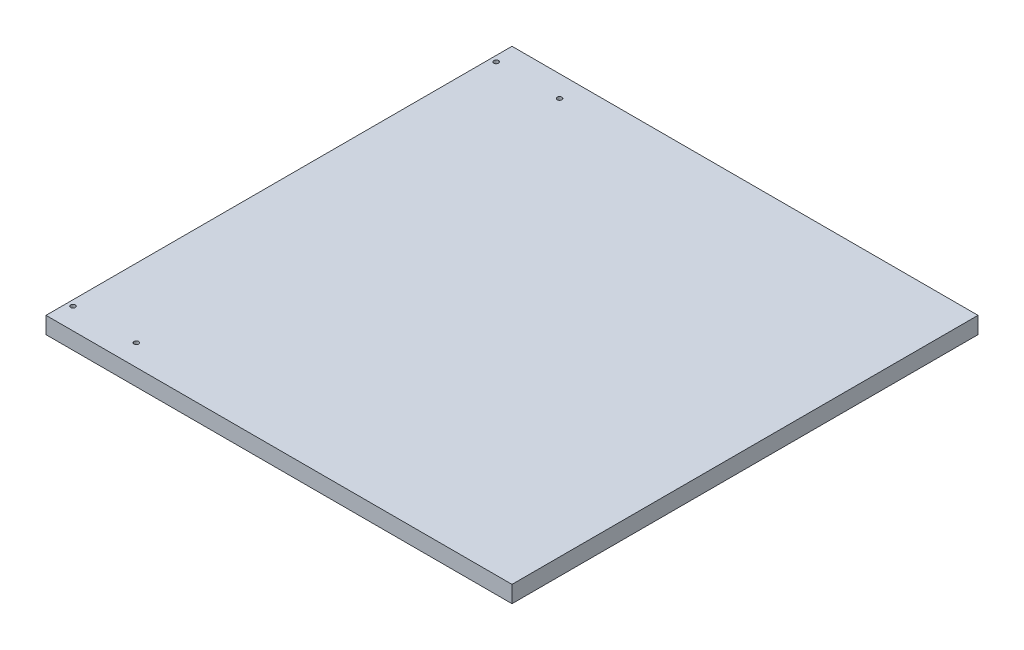
SolidWorks part; units mm, degrees
ref_plane "Front Plane" through (0, 0, 0) normal (0, 0, 1) x (1, 0, 0)
ref_plane "Top Plane" through (0, 0, 0) normal (0, 1, 0) x (1, 0, 0)
ref_plane "Right Plane" through (0, 0, 0) normal (1, 0, 0) x (0, 0, -1)
sketch "Sketch1" plane through (0, 0, 0) normal (0, 1, 0) x (1, 0, 0)
  line L1 (250, -250) -> (-250, -250)
  line L2 (250, -250) -> (250, 250)
  line L3 (250, 250) -> (-250, 250)
  line L4 (-250, -250) -> (-250, 250)
  line L5 (250, -250) -> (-250, 250) construction
  line L6 (250, 250) -> (-250, -250) construction
  point P0 (0, 0)
  dimension "D1" = 500
  dimension "D2" = 500
extrude "Boss-Extrude2" add sketch "Sketch1" along normal mid plane 18
sketch "Sketch2" plane through (0, 9, 0) normal (0, 1, 0) x (1, 0, 0)
  line L2 (290.8367, 0) -> (-330.2014, 0) construction
  line L4 (-210, 272.2904) -> (-210, 197.4986) construction
  circle A2 centre (-176, 227) radius 2.5
  circle A3 centre (-244, 227) radius 2.5
  circle A4 centre (-244, -227) radius 2.5
  circle A5 centre (-176, -227) radius 2.5
extrude "Cut-Extrude1" cut sketch "Sketch2" against normal through all
chamfer "Chamfer1" distance 2 angle 45 4 edges at (-176, -9, -224.5) (-244, -9, -229.5) (-176, -9, 224.5) (-244, -9, 229.5)
